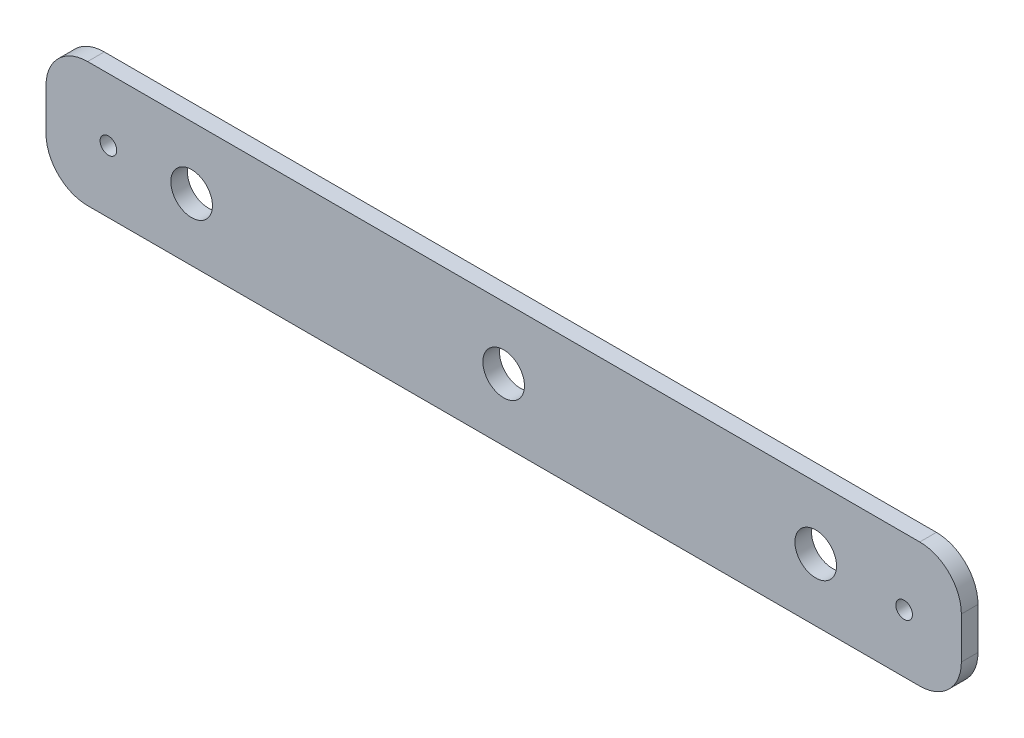
SolidWorks part; units mm, degrees
ref_plane "Front Plane" through (0, 0, 0) normal (0, 0, 1) x (1, 0, 0)
ref_plane "Top Plane" through (0, 0, 0) normal (0, 1, 0) x (1, 0, 0)
ref_plane "Right Plane" through (0, 0, 0) normal (1, 0, 0) x (0, 0, -1)
sketch "Sketch1" plane through (0, 0, 0) normal (0, 0, 1) x (1, 0, 0)
  line L1 (0, 0) -> (-220, 0)
  line L2 (0, 0) -> (0, -30)
  line L3 (0, -30) -> (-220, -30)
  line L4 (-220, 0) -> (-220, -30)
  circle A0 centre (-205, -15) radius 2
  circle A1 centre (-13.75, -16) radius 2
  dimension "D3" = 4
  dimension "D6" = 4
  dimension "D1" = 220
  dimension "D2" = 30
  dimension "D4" = 15
  dimension "D5" = 15
  dimension "D7" = 13.75
  dimension "D8" = 16
extrude "Boss-Extrude1" add sketch "Sketch1" along normal blind 4
fillet "Fillet1" radius 10 4 edges at (0, 0, 2) (0, -30, 2) (-220, -30, 2) (-220, 0, 2)
sketch "Sketch2" plane through (0, 0, 4) normal (0, 0, 1) x (1, 0, 0)
  line L0 (-220, -10) -> (-220, -20) construction
  line L2 (-210, -30) -> (-10, -30) construction
  circle A0 centre (-185, -15) radius 5
  circle A1 centre (-110, -15) radius 5
  circle A2 centre (-35, -15) radius 5
  point P8 (-220, -15)
  dimension "D4" = 10
  dimension "D5" = 10
  dimension "D6" = 10
  dimension "D1" = 110
  dimension "D2" = 75
  dimension "D3" = 75
  dimension "D7" = 15
  dimension "D8" = 15
  dimension "D9" = 15
extrude "Cut-Extrude1" cut sketch "Sketch2" against normal blind 10
